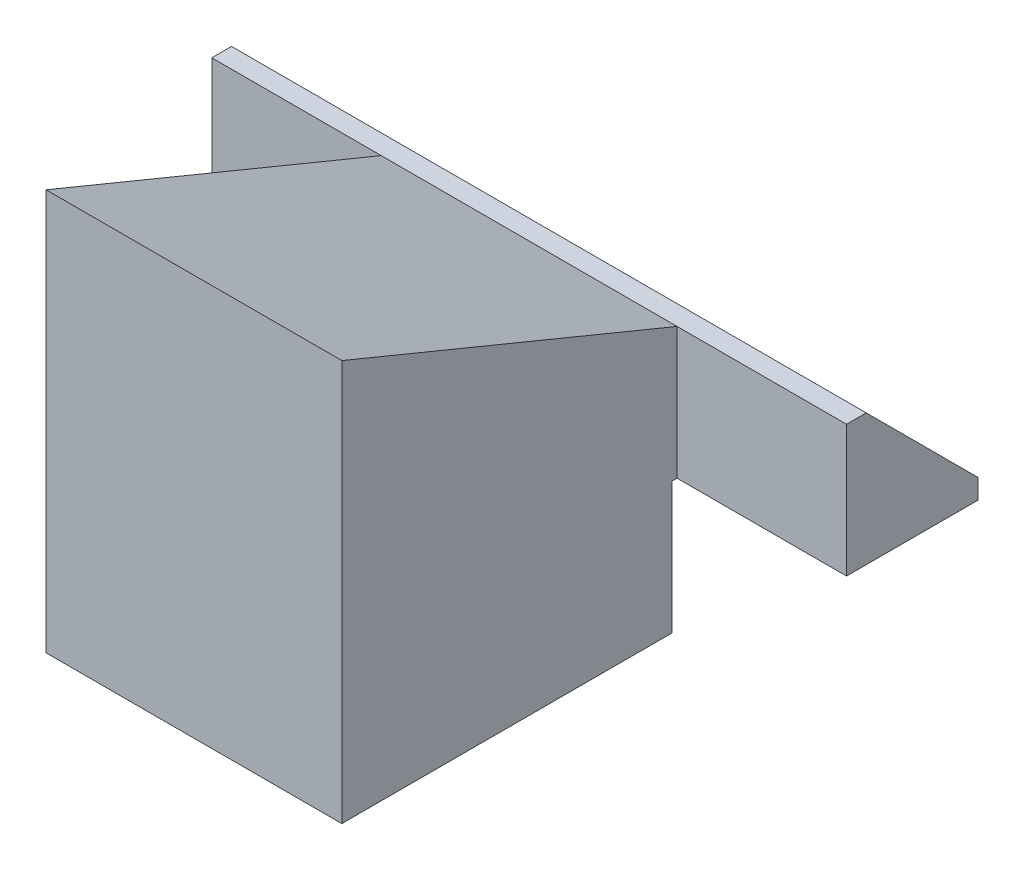
SolidWorks part; units mm, degrees
ref_plane "정면" through (0, 0, 0) normal (0, 0, 1) x (1, 0, 0)
ref_plane "윗면" through (0, 0, 0) normal (0, 1, 0) x (1, 0, 0)
ref_plane "우측면" through (0, 0, 0) normal (1, 0, 0) x (0, 0, -1)
sketch "스케치1" plane through (0, 0, 0) normal (0, 0, 1) x (1, 0, 0)
  line L1 (-48.2791, 20) -> (48.2791, 20)
  line L2 (-48.2791, 20) -> (-48.2791, -20)
  line L3 (-48.2791, -20) -> (48.2791, -20)
  line L4 (48.2791, 20) -> (48.2791, -20)
  line L5 (-48.2791, 20) -> (48.2791, -20) construction
  line L6 (-48.2791, -20) -> (48.2791, 20) construction
  point P0 (0, 0)
  dimension "D1" = 40
extrude "보스-돌출1" add sketch "스케치1" along normal blind 51
sketch "스케치2" plane through (0, 0, 0) normal (0, 0, -1) x (-1, 0, 0)
  line L0 (48.2791, 20) -> (48.2791, -20) construction
  line L1 (-48.2791, 20) -> (48.2791, 20)
  line L2 (-48.2791, 20) -> (-48.2791, 0)
  line L3 (-48.2791, 0) -> (48.2791, 0)
  line L4 (48.2791, 20) -> (48.2791, 0)
extrude "보스-돌출2" add sketch "스케치2" along normal blind 20
sketch "스케치4" plane through (0, 20, 0) normal (0, 1, 0) x (1, 0, 0)
  line L5 (-48.2791, 20) -> (48.2791, 20) construction
  line L10 (-43.2791, 20) -> (-5, 20)
  line L11 (-43.2791, 20) -> (-43.2791, 3)
  line L12 (-43.2791, 3) -> (-5, 3)
  line L13 (-5, 20) -> (-5, 3)
  line L14 (-48.2791, -51) -> (-48.2791, 20) construction
  line L15 (5, 20) -> (43.2791, 20)
  line L16 (5, 20) -> (5, 3)
  line L17 (5, 3) -> (43.2791, 3)
  line L18 (43.2791, 20) -> (43.2791, 3)
  line L19 (48.2791, -51) -> (48.2791, 20) construction
  dimension "D1" = 5
  dimension "D2" = 10
  dimension "D3" = 5
  dimension "D4" = 5
  dimension "D5" = 17
  dimension "D6" = 17
extrude "컷-돌출1" cut sketch "스케치4" against normal blind 17
sketch "스케치6" plane through (48.2791, 0, 0) normal (1, 0, 0) x (0, 0, -1)
  line L5 (3, 20) -> (20, 20)
  line L6 (-51, 20) -> (20, 20) construction
  line L7 (20, 20) -> (20, 3)
  line L8 (20, 20) -> (20, 0) construction
  line L9 (20, 3) -> (3, 20)
  dimension "D1" = 0
  dimension "D2" = 0
extrude "컷-돌출2" cut sketch "스케치6" against normal through all
hole_wizard "M4 나사 구멍1" positions "스케치7" profile "스케치8" tap size "M4" standard "KS"
sketch "스케치7" plane through (0, 3, 0) normal (0, 1, 0) x (1, 0, 0)
  line L0 (-43.2791, 20) -> (-43.2791, 3) construction
  line L1 (-5, 3) -> (-5, 20) construction
  line L2 (5, 20) -> (5, 3) construction
  line L3 (43.2791, 3) -> (43.2791, 20) construction
  line L4 (43.2791, 20) -> (5, 20) construction
  line L5 (-5, 20) -> (-43.2791, 20) construction
  point P0 (-33.2791, 10)
  point P2 (-15, 10)
  point P4 (15, 10)
  point P6 (33.2791, 10)
  dimension "D1" = 10
  dimension "D2" = 10
  dimension "D3" = 10
  dimension "D4" = 10
  dimension "D5" = 10
  dimension "D6" = 10
  dimension "D7" = 10
  dimension "D8" = 10
sketch "스케치8" plane through (-33.2791, 3, -10) normal (1, 0, 0) x (0, 0, 1)
  line L0 (0, 0) -> (0, 11.2416)
  line L1 (0, 11.2416) -> (1.9, 10.1)
  line L2 (1.9, 10.1) -> (1.9, 0)
  line L5 (1.9, 0) -> (0, 0)
  line L10 (0, 11.2416) -> (-1.9, 10.1) construction
  line L11 (0, -6.35) -> (0, 107.95) construction
  dimension "탭 드릴 지름" = 3.8
  dimension "탭 드릴 깊이" = 10.1
  dimension "드릴 각도" = 118
cosmetic thread "구멍 나사산1" parameters "D1"=8, "D2"=4
cosmetic thread "구멍 나사산2" parameters "D1"=8, "D2"=4
cosmetic thread "구멍 나사산3" parameters "D1"=8, "D2"=4
cosmetic thread "구멍 나사산4" parameters "D1"=8, "D2"=4
sketch "스케치9" plane through (0, 0, 51) normal (0, 0, 1) x (1, 0, 0)
  line L0 (-48.2791, 20) -> (-48.2791, -20) construction
  line L1 (-48.2791, 20) -> (-22.5, 20)
  line L2 (-48.2791, 20) -> (-48.2791, -20)
  line L3 (-48.2791, -20) -> (-22.5, -20)
  line L4 (-22.5, 20) -> (-22.5, -20)
  line L5 (48.2791, 20) -> (-48.2791, 20) construction
  line L6 (22.5, 20) -> (48.2791, 20)
  line L7 (22.5, 20) -> (22.5, -20)
  line L8 (22.5, -20) -> (48.2791, -20)
  line L9 (48.2791, 20) -> (48.2791, -20)
  line L10 (48.2791, -20) -> (48.2791, 20) construction
  line L11 (-48.2791, -20) -> (48.2791, -20) construction
  dimension "D1" = 45
  dimension "D2" = 22.5
extrude "컷-돌출3" cut sketch "스케치9" against normal up to surface (51 mm away) up to face at (0, -10, 0)
sketch "스케치10" plane through (-22.5, 0, 0) normal (-1, 0, 0) x (0, 0, 1)
  line L4 (51, 20) -> (51, 41)
  line L5 (51, 41) -> (0, 20)
  line L6 (0, 20) -> (51, 20)
  dimension "D1" = 21
extrude "보스-돌출4" add sketch "스케치10" against normal up to vertex
sketch "스케치11" plane through (0, 0, 0) normal (0, 0, -1) x (-1, 0, 0)
  line L1 (22.5, -20) -> (-22.5, -20)
  line L2 (22.5, -20) -> (22.5, 0)
  line L3 (22.5, 0) -> (-22.5, 0)
  line L4 (-22.5, -20) -> (-22.5, 0)
extrude "컷-돌출4" cut sketch "스케치11" against normal blind 0.8
